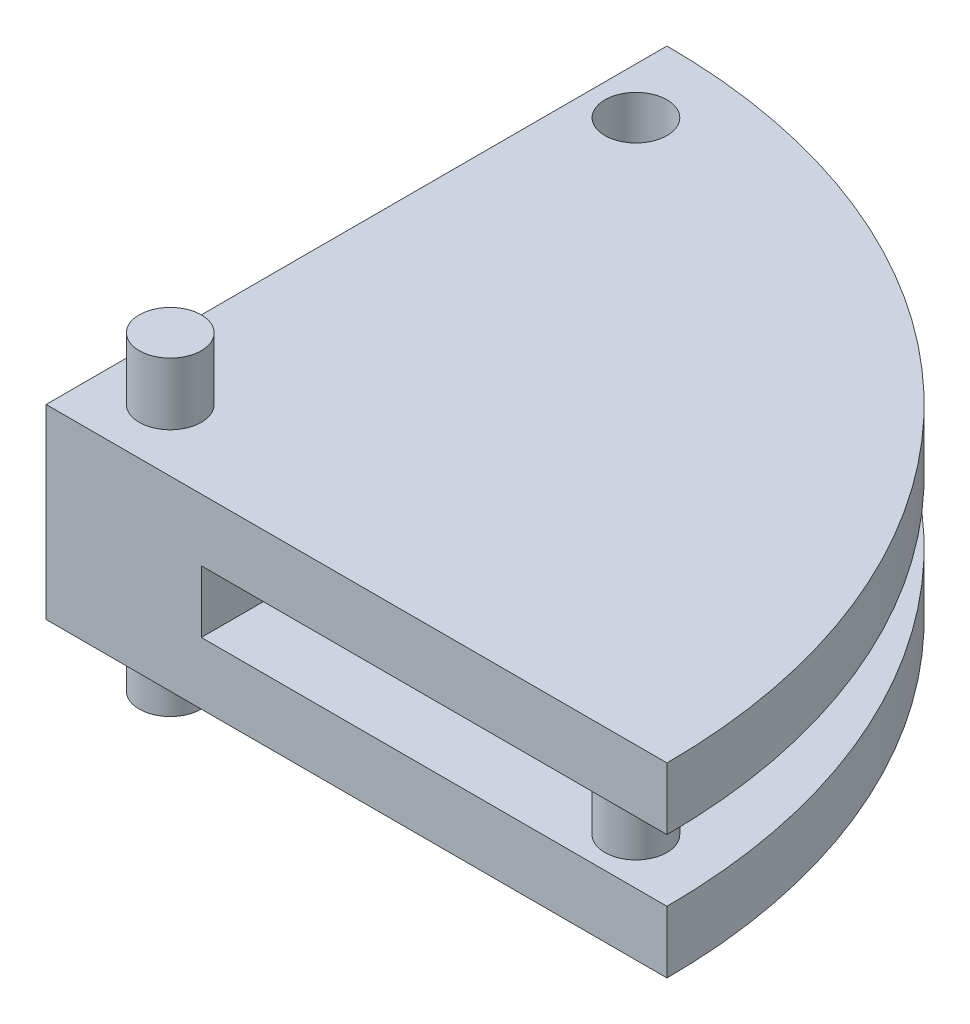
SolidWorks part; units mm, degrees
ref_plane "Front Plane" through (0, 0, 0) normal (0, 0, 1) x (1, 0, 0)
ref_plane "Top Plane" through (0, 0, 0) normal (0, 1, 0) x (1, 0, 0)
ref_plane "Right Plane" through (0, 0, 0) normal (1, 0, 0) x (0, 0, -1)
sketch "Sketch1" plane through (0, 0, 0) normal (0, 1, 0) x (1, 0, 0)
  line L0 (0, 0) -> (10, 0)
  line L1 (0, 0) -> (0, 10)
  arc A0 (0, 10) -> (10, 0) centre (0, 0) cw
  dimension "D1" = 10
extrude "Boss-Extrude1" add sketch "Sketch1" along normal blind 1
sketch "Sketch2" plane through (0, 1, 0) normal (0, 1, 0) x (1, 0, 0)
  line L0 (0, 0) -> (10, 0) construction
  line L1 (0, 0) -> (2.5, 0)
  line L2 (0, 0) -> (0, 2.5)
  line L3 (0, 2.5) -> (2.5, 2.5)
  line L4 (2.5, 0) -> (2.5, 2.5)
  circle A0 centre (8.75, 0.75) radius 0.5
  dimension "D3" = 1.25
  dimension "D1" = 2.5
  dimension "D2" = 2.5
  dimension "D4" = 0.75
extrude "Boss-Extrude2" add sketch "Sketch2" along normal blind 1
sketch "Sketch3" plane through (0, 2, 0) normal (0, 1, 0) x (1, 0, 0)
  line L0 (0, 10) -> (0, 0)
  line L1 (0, 0) -> (10, 0)
  arc A0 (0, 10) -> (10, 0) centre (0, 0) cw
  arc A1 (10, 0) -> (0, 10) centre (0, 0) ccw construction
extrude "Boss-Extrude3" add sketch "Sketch3" along normal blind 1
sketch "Sketch4" plane through (0, 3, 0) normal (0, 1, 0) x (1, 0, 0)
  circle A0 centre (0.75, 8.75) radius 0.5
  dimension "D3" = 1
  dimension "D1" = 1.25
  dimension "D2" = 0.75
extrude "Cut-Extrude1" cut sketch "Sketch4" against normal through all
sketch "Sketch5" plane through (0, 3, 0) normal (0, 1, 0) x (1, 0, 0)
  line L0 (0, 0) -> (10, 0) construction
  line L1 (0, 10) -> (0, 0) construction
  circle A0 centre (1, 1) radius 0.5
  dimension "D1" = 1
  dimension "D2" = 1
  dimension "D3" = 1
extrude "Boss-Extrude4" add sketch "Sketch5" along normal blind 1 and the other way blind 4
